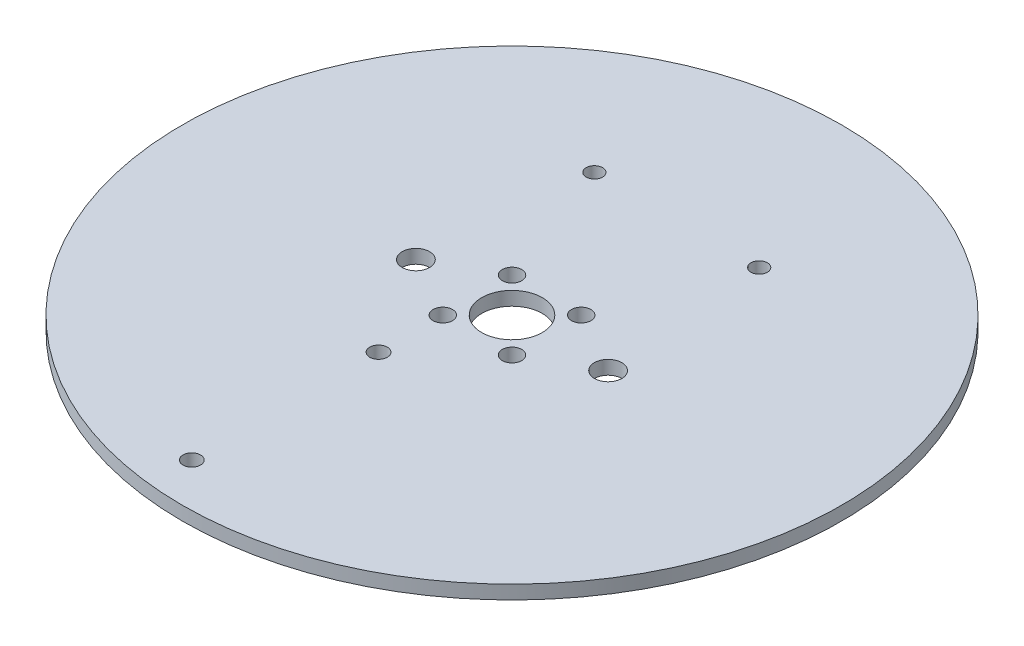
SolidWorks part; units mm, degrees
ref_plane "Front Plane" through (0, 0, 0) normal (0, 0, 1) x (1, 0, 0)
ref_plane "Top Plane" through (0, 0, 0) normal (0, 1, 0) x (1, 0, 0)
ref_plane "Right Plane" through (0, 0, 0) normal (1, 0, 0) x (0, 0, -1)
sketch "Sketch1" plane through (0, 0, 0) normal (0, 1, 0) x (1, 0, 0)
  circle A0 centre (0, 0) radius 76.2
  dimension "D1" = 152.4
extrude "Boss-Extrude1" add sketch "Sketch1" along normal blind 3.175
sketch "Sketch2" plane through (0, 3.175, 0) normal (0, 1, 0) x (1, 0, 0)
  circle A0 centre (0, 0) radius 7
extrude "Cut-Extrude1" cut sketch "Sketch2" against normal up to next
sketch "Sketch3" plane through (0, 3.175, 0) normal (0, 1, 0) x (1, 0, 0)
  circle A4 centre (6.9862, -65.9416) radius 2.032 construction
  circle A5 centre (7.363, -22.7632) radius 2.032 construction
  circle A6 centre (6.9862, -65.9416) radius 2.032
  circle A7 centre (7.363, -22.7632) radius 2.032
sketch "Sketch4" plane through (0, 3.175, 0) normal (0, 1, 0) x (1, 0, 0)
  circle A0 centre (-22.225, 0) radius 3.175 construction
  circle A1 centre (22.225, 0) radius 3.175 construction
  circle A2 centre (-22.225, 0) radius 3.175
  circle A3 centre (22.225, 0) radius 3.175
extrude "Cut-Extrude3" cut sketch "Sketch4" against normal through all both
hole_wizard "M4 Clearance Hole1" positions "Sketch5" profile "Sketch6" hole size "M4" standard "ANSI Metric" end condition up to next
sketch "Sketch5" plane through (0, 3.175, 0) normal (0, 1, 0) x (1, 0, 0)
  line L0 (-8, 8) -> (8, 8) construction
  line L1 (8, 8) -> (8, -8) construction
  line L2 (0, -1.7463) -> (0, 1.7463) construction
  line L4 (-1.7463, 0) -> (1.7463, 0) construction
  point P0 (-8, 8)
  point P2 (8, 8)
  point P4 (8, -8)
  point P6 (-8, -8)
  point P21 (0, 8)
  point P26 (8, 0)
  dimension "D1" = 16
  dimension "D2" = 16
sketch "Sketch6" plane through (-8, 3.175, -8) normal (1, 0, 0) x (0, 0, 1)
  line L0 (0, 0) -> (0, 3.175)
  line L1 (0, 3.175) -> (2.25, 3.175)
  line L2 (2.25, 3.175) -> (2.25, 0)
  line L5 (2.25, 0) -> (0, 0)
  line L11 (0, -6.35) -> (0, 107.95) construction
  dimension "Thru Hole Dia." = 4.5
  dimension "Thru Hole Depth" = 3.175
sketch "Sketch8" plane through (0, 3.175, 0) normal (0, 1, 0) x (1, 0, 0)
  circle A0 centre (19.05, 38.1) radius 1.8987 construction
  circle A1 centre (-19.05, 38.1) radius 1.8987 construction
  circle A2 centre (19.05, 38.1) radius 1.8987
  circle A3 centre (-19.05, 38.1) radius 1.8987
extrude "Cut-Extrude4" cut sketch "Sketch8" against normal up to next
sketch "Sketch9" plane through (0, 0, 0) normal (0, -1, 0) x (1, 0, 0)
  circle A0 centre (-8, 22.86) radius 2.032 construction
  circle A1 centre (-8, 66.04) radius 2.032 construction
  circle A2 centre (-8, 22.86) radius 2.032
  circle A3 centre (-8, 66.04) radius 2.032
extrude "Cut-Extrude5" cut sketch "Sketch9" against normal up to next
